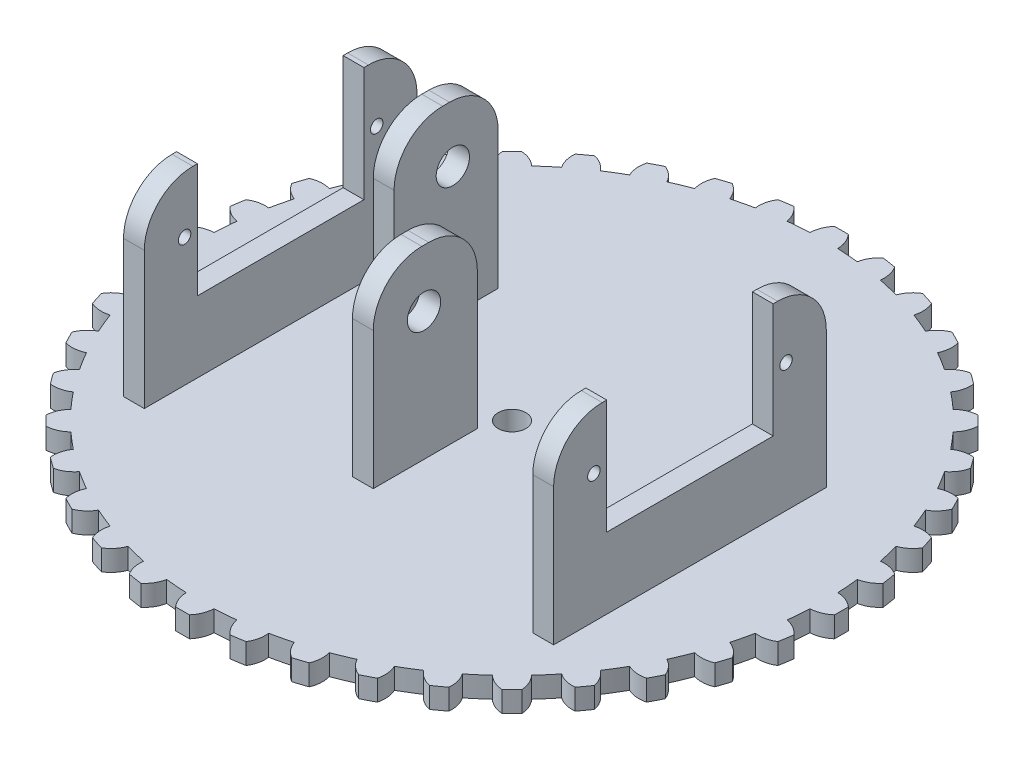
SolidWorks part; units mm, degrees
ref_plane "Front Plane" through (0, 0, 0) normal (0, 0, 1) x (1, 0, 0)
ref_plane "Top Plane" through (0, 0, 0) normal (0, 1, 0) x (1, 0, 0)
ref_plane "Right Plane" through (0, 0, 0) normal (1, 0, 0) x (0, 0, -1)
sketch "Sketch1" plane through (0, 0, 0) normal (0, 1, 0) x (1, 0, 0)
  circle A0 centre (0, 0) radius 45
  circle A1 centre (0, 0) radius 2
  dimension "D1" = 90
  dimension "D2" = 4
extrude "Boss-Extrude1" add sketch "Sketch1" along normal blind 3
sketch "Sketch2" plane through (0, 0, 0) normal (0, 1, 0) x (1, 0, 0)
  line L0 (0, 0) -> (0, 45) construction
  arc A6 (1, 47.4895) -> (-1, 47.4895) centre (0, 0) ccw
  arc A7 (-1, 47.4895) -> (-2, 44.9555) centre (1.9984, 44.8419) ccw
  circle A8 centre (0, 0) radius 45 construction
  arc A9 (1, 47.4895) -> (2, 44.9555) centre (-1.9984, 44.8419) cw
  circle A10 centre (0, 0) radius 45
  arc A11 (-2, 44.9555) -> (2, 44.9555) centre (0, 0) cw
  point P0 (1, 47.4895)
  dimension "D1" = 95
  dimension "D4" = 4
  dimension "D2" = 2
  dimension "D3" = 1
extrude "Boss-Extrude2" add sketch "Sketch2" along normal blind 3
pattern_circular "CirPattern2" count 40 over 360 about axis through (0, 0, 0) along (0, 1, 0) of "Boss-Extrude2"
sketch "Sketch4" plane through (0, 3, 0) normal (0, 1, 0) x (1, 0, 0)
  line L0 (21, 25) -> (31, 25)
  line L1 (-31, -25) -> (31, -25)
  line L2 (-31, -25) -> (-31, 25)
  line L3 (31, -25) -> (31, 25)
  line L4 (0, -25) -> (0, 25) construction
  line L5 (21, 25) -> (-31, 25)
  line L6 (21, 25) -> (6, 25)
  line L7 (6, 25) -> (6, 17.5)
  line L8 (6, 17.5) -> (-11.15, 17.5)
  line L9 (-11.15, 17.5) -> (-11.15, 5)
  line L10 (-11.15, 5) -> (-31, 5)
  line L11 (-31, 5) -> (-31, -25)
  line L12 (-31, -25) -> (-28, -25)
  line L13 (-31, -25) -> (-31, 14.3)
  line L14 (-31, 14.3) -> (-28, 14.3)
  line L15 (-28, -25) -> (-28, 14.3)
  line L16 (31, 14.3) -> (28, 14.3)
  line L17 (28, -25) -> (28, 14.3)
  line L18 (31, -25) -> (28, -25)
  line L19 (31, -25) -> (31, 14.3)
  line L21 (-4.5, -18.5) -> (-1.5, -18.5)
  line L22 (-4.5, -18.5) -> (-4.5, -3.5)
  line L23 (-4.5, -3.5) -> (-1.5, -3.5)
  line L24 (-1.5, -18.5) -> (-1.5, -3.5)
  line L25 (-4.5, -18.5) -> (-1.5, -3.5) construction
  line L26 (-4.5, -3.5) -> (-1.5, -18.5) construction
  line L27 (-20.5, 15.5) -> (-17.5, 15.5)
  line L28 (-20.5, 15.5) -> (-20.5, 0.5)
  line L29 (-20.5, 0.5) -> (-17.5, 0.5)
  line L30 (-17.5, 15.5) -> (-17.5, 0.5)
  line L31 (-20.5, 15.5) -> (-17.5, 0.5) construction
  line L32 (-20.5, 0.5) -> (-17.5, 15.5) construction
  circle A1 centre (0, 0) radius 1.85
  point P4 (21, 25)
  point P9 (0, 0)
  point P19 (0, -25)
  point P20 (-31, 0)
  point P25 (0, -11)
  point P30 (-19, 8)
  point P35 (0, 0)
  point P36 (-3, -11)
  point P38 (-15.2676, -4.1414)
  dimension "D1" = 50
  dimension "D2" = 52
  dimension "D3" = 10
  dimension "D4" = 39.3
  dimension "D5" = 3
  dimension "D6" = 15
  dimension "D7" = 3
  dimension "D8" = 14
  dimension "D9" = 19
  dimension "D10" = 15
  dimension "D11" = 3
  dimension "D12" = 9
  dimension "D13" = 3
extrude "Boss-Extrude3" add sketch "Sketch4" along normal blind 26.75 contours L10 L15 L14 L2 | L1 L15 L10 L2 | L17 L1 L3 L16 | L28 L27 L30 L29 | L22 L21 L24 L23
fillet "Fillet1" radius 7 4 edges at (-29.5, 29.75, -14.3) (29.5, 29.75, -14.3) (29.5, 29.75, 25) (-29.5, 29.75, 25)
sketch "Sketch5" plane through (-31, 0, 0) normal (-1, 0, 0) x (0, 0, 1)
  line L0 (-6.65, 29.75) -> (-6.65, 13.25)
  line L1 (18, 29.75) -> (-7.3, 29.75) construction
  line L2 (-6.65, 13.25) -> (17.35, 13.25)
  line L3 (17.35, 13.25) -> (17.35, 29.75)
  line L4 (17.35, 29.75) -> (-6.65, 29.75)
  line L5 (-14.3, 22.75) -> (-14.3, 3) construction
  line L6 (5.35, 13.25) -> (5.35, 29.75) construction
  circle A0 centre (-8.5, 21.5) radius 0.9
  circle A1 centre (19.2, 21.5) radius 0.9
  point P11 (-6.65, 21.5)
  dimension "D4" = 1.8
  dimension "D1" = 7.65
  dimension "D2" = 24
  dimension "D3" = 13.25
  dimension "D5" = 1.85
extrude "Cut-Extrude1" cut sketch "Sketch5" against normal up to vertex (3 mm away)
mirror "Mirror2" about plane through (0, 0, 0) normal (1, 0, 0) of "Cut-Extrude1"
sketch "Sketch7" plane through (-17.5, 0, 0) normal (1, 0, 0) x (0, 0, -1)
  line L0 (15.5, 3) -> (0.5, 3) construction
  circle A0 centre (8.9732, 21.5) radius 2.4
  dimension "D2" = 4.8
  dimension "D1" = 18.5
extrude "Cut-Extrude2" cut sketch "Sketch7" against normal up to next
sketch "Sketch8" plane through (-1.5, 0, 0) normal (1, 0, 0) x (0, 0, -1)
  line L0 (-18.5, 3) -> (-3.5, 3) construction
  circle A0 centre (-11.1873, 21.5) radius 2.4
  dimension "D1" = 4.8
  dimension "D2" = 18.5
extrude "Cut-Extrude3" cut sketch "Sketch8" against normal up to next
fillet "Fillet3" radius 7 4 edges at (-19, 29.75, -15.5) (-19, 29.75, -0.5) (-3, 29.75, 3.5) (-3, 29.75, 18.5)
